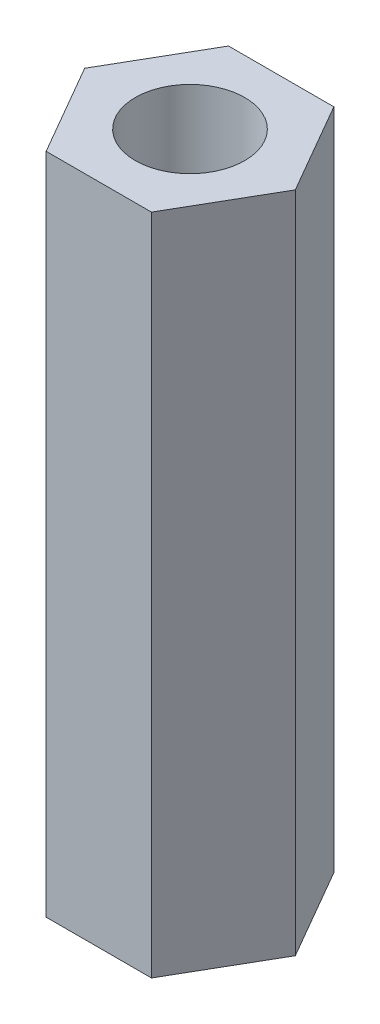
SolidWorks part; units mm, degrees
ref_plane "Front Plane" through (0, 0, 0) normal (0, 0, 1) x (1, 0, 0)
ref_plane "Top Plane" through (0, 0, 0) normal (0, 1, 0) x (1, 0, 0)
ref_plane "Right Plane" through (0, 0, 0) normal (1, 0, 0) x (0, 0, -1)
sketch "Sketch1" plane through (0, 0, 0) normal (0, 1, 0) x (1, 0, 0)
  line L1 (1.5877, 2.75) -> (-1.5877, 2.75)
  line L2 (-1.5877, 2.75) -> (-3.1754, 0)
  line L3 (-3.1754, 0) -> (-1.5877, -2.75)
  line L4 (-1.5877, -2.75) -> (1.5877, -2.75)
  line L5 (1.5877, -2.75) -> (3.1754, 0)
  line L6 (3.1754, 0) -> (1.5877, 2.75)
  circle A0 centre (0, 0) radius 2.75 construction
  circle A1 centre (0, 0) radius 1.65
  point P10 (0, 0)
  dimension "D1" = 3.3
  dimension "D2" = 5.5
extrude "Boss-Extrude1" add sketch "Sketch1" along normal blind 20
